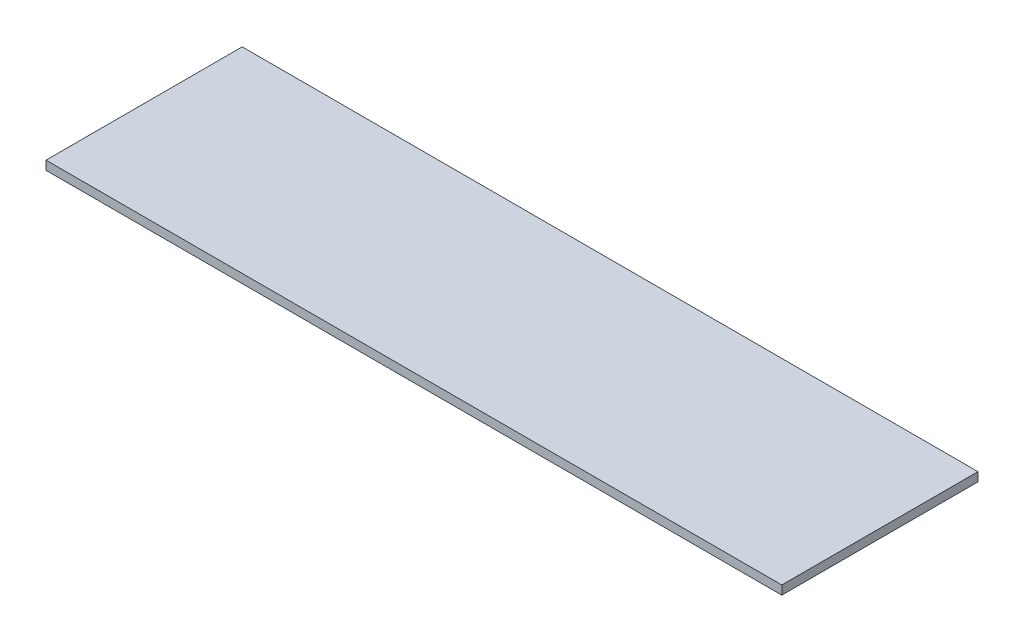
SolidWorks part; units mm, degrees
ref_plane "Front Plane" through (0, 0, 0) normal (0, 0, 1) x (1, 0, 0)
ref_plane "Top Plane" through (0, 0, 0) normal (0, 1, 0) x (1, 0, 0)
ref_plane "Right Plane" through (0, 0, 0) normal (1, 0, 0) x (0, 0, -1)
sketch "Esquisse1" plane through (0, 0, 0) normal (0, 1, 0) x (1, 0, 0)
  line L1 (-750, 200) -> (750, 200)
  line L2 (-750, 200) -> (-750, -200)
  line L3 (-750, -200) -> (750, -200)
  line L4 (750, 200) -> (750, -200)
  line L5 (-750, 200) -> (750, -200) construction
  line L6 (-750, -200) -> (750, 200) construction
  point P0 (0, 0)
extrude "Boss.-Extru.1" add sketch "Esquisse1" along normal blind 18
